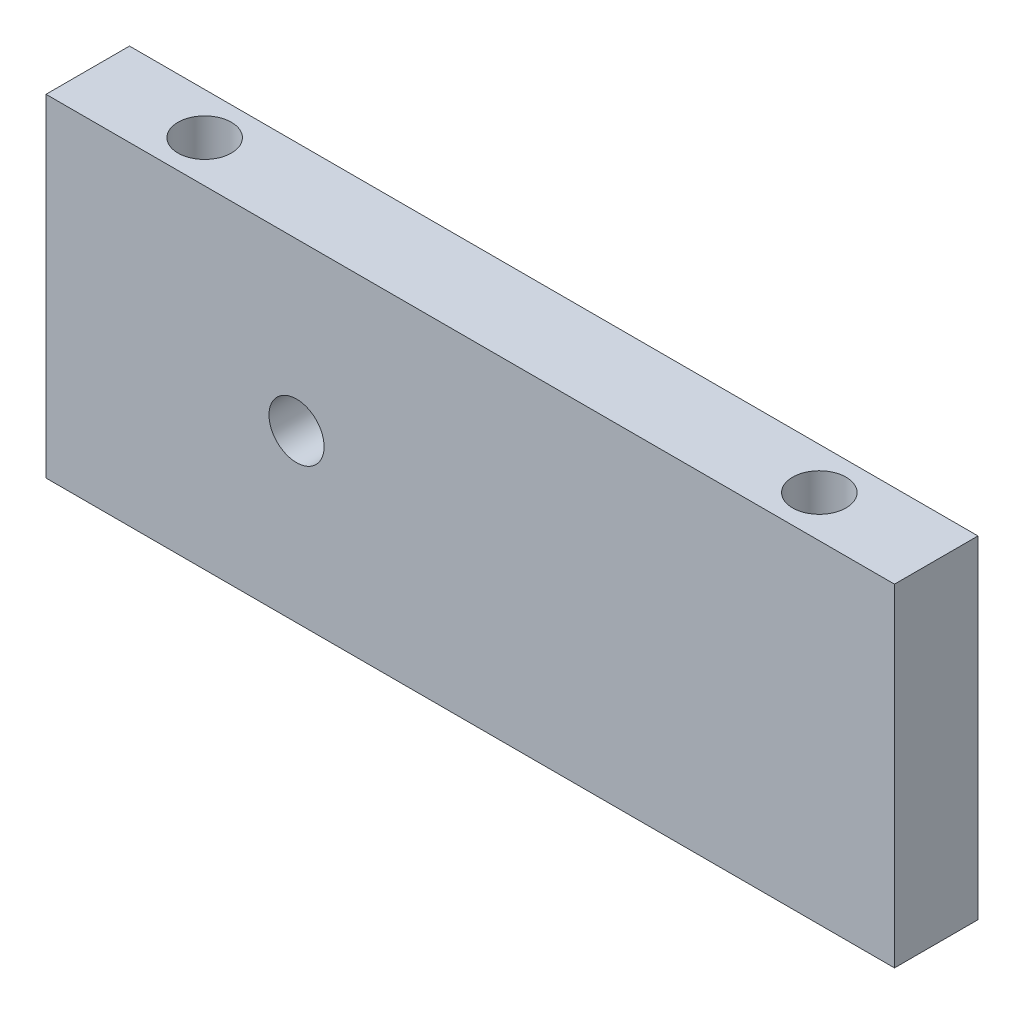
SolidWorks part; units mm, degrees
material "Alliage 1060"
ref_plane "Plan de face" through (0, 0, 0) normal (0, 0, 1) x (1, 0, 0)
ref_plane "Plan de dessus" through (0, 0, 0) normal (0, 1, 0) x (1, 0, 0)
ref_plane "Plan de droite" through (0, 0, 0) normal (1, 0, 0) x (0, 0, -1)
sketch "Esquisse1" plane through (0, 0, 0) normal (0, 0, 1) x (1, 0, 0)
  line L0 (35.8, 19.9) -> (35.8, 0) construction
  line L1 (-15, 19.9) -> (35.8, 19.9)
  line L2 (-15, 19.9) -> (-15, 0)
  line L3 (-15, 0) -> (35.8, 0)
  line L4 (35.8, 19.9) -> (35.8, 0)
  line L5 (35.8, 19.9) -> (30.8, 19.9) construction
  line L6 (-15, 19.9) -> (-15, 0) construction
extrude "Extrusion1" add sketch "Esquisse1" along normal blind 5
hole_wizard "Trou taraudé M4x0.71" positions "Esquisse3" profile "Esquisse2" tap size "M4x0.7" standard "Ansi Métrique" end condition through all
sketch "Esquisse3" plane through (0, 0, 5) normal (0, 0, 1) x (1, 0, 0)
  circle A2 centre (0, 9.95) radius 2.5 construction
  point P0 (0, 9.95)
sketch "Esquisse2" plane through (0, 9.95, 5) normal (1, 0, 0) x (0, -1, 0)
  line L0 (0, 0) -> (0, 5)
  line L1 (0, 5) -> (1.65, 5)
  line L2 (1.65, 5) -> (1.65, 0)
  line L5 (1.65, 0) -> (0, 0)
  line L11 (0, -6.35) -> (0, 107.95) construction
  dimension "Diamètre du trou pour taraudage jusqu'au prochain" = 3.3
  dimension "Profondeur du trou pour taraudage jusqu'au prochain" = 5
cosmetic thread "Filetage de perçage4" parameters "D1"=5, "D2"=4
sketch "Esquisse4" plane through (0, 19.9, 0) normal (0, 1, 0) x (1, 0, 0)
  circle A0 centre (-8, -2.5) radius 1.6 construction
  circle A1 centre (-8, -2.5) radius 1.6
  circle A2 centre (28.8, -2.5) radius 1.6 construction
  circle A3 centre (28.8, -2.5) radius 1.6
extrude "Enlèv. mat.-Extru.1" cut sketch "Esquisse4" against normal through all
